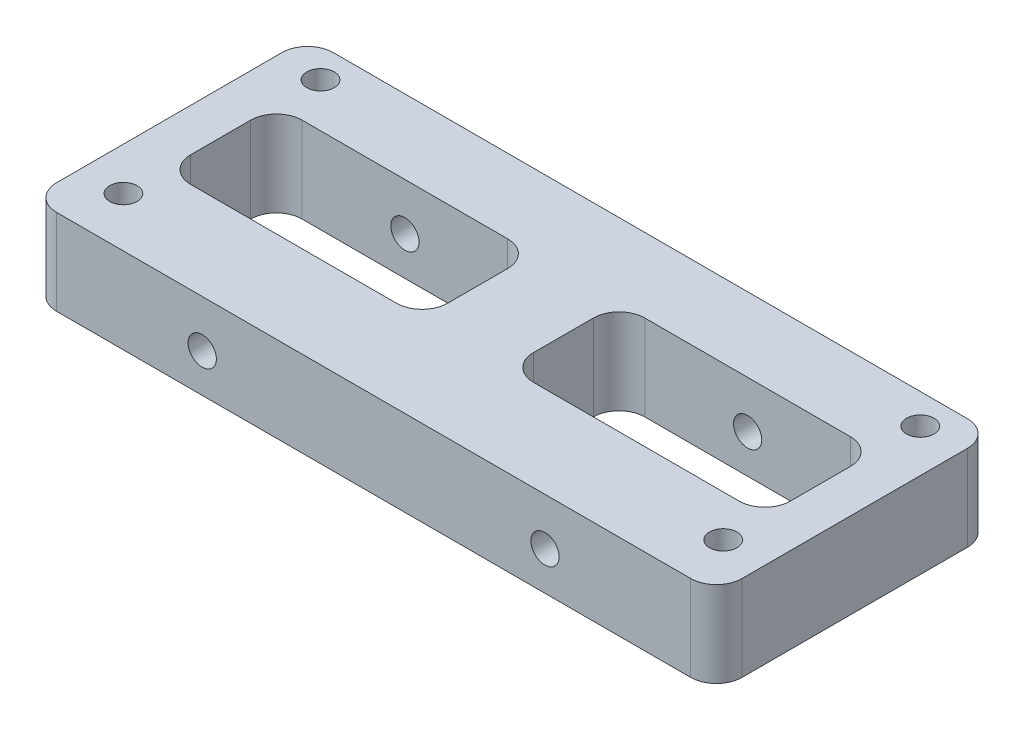
SolidWorks part; units mm, degrees
material "ABS"
ref_plane "前视基准面" through (0, 0, 0) normal (0, 0, 1) x (1, 0, 0)
ref_plane "上视基准面" through (0, 0, 0) normal (0, 1, 0) x (1, 0, 0)
ref_plane "右视基准面" through (0, 0, 0) normal (1, 0, 0) x (0, 0, -1)
other "Configuration Table"
sketch "草图1" plane through (0, 0, 0) normal (0, 1, 0) x (1, 0, 0)
  line L0 (-50.2114, 11.65) -> (54.5041, 11.65) construction
  line L1 (-40, -17.15) -> (40, -17.15) construction
  line L2 (-40, -17.15) -> (-40, 17.15)
  line L3 (-40, 17.15) -> (40, 17.15)
  line L4 (40, -17.15) -> (40, 17.15)
  line L5 (-40, -17.15) -> (40, 17.15) construction
  line L6 (-40, 17.15) -> (40, -17.15) construction
  line L7 (-47.7398, -11.35) -> (53.8537, -11.35) construction
  line L8 (-35, 11.65) -> (-35, -11.35) construction
  line L9 (0, 39.122) -> (0, -35.2195) construction
  line L10 (-40, -17.15) -> (-20, -17.15)
  line L15 (-15, -6.5) -> (15, 6.5) construction
  line L16 (-15, 6.5) -> (15, -6.5) construction
  line L17 (-20, -17.15) -> (20, -17.15) construction
  line L24 (-20, -17.15) -> (20, -17.15)
  line L28 (20, -17.15) -> (40, -17.15)
  line L29 (35, -11.35) -> (35, 11.65) construction
  line L30 (47.8523, 0) -> (-46.2737, 0) construction
  line L31 (-35, 6.5) -> (-5, 6.5)
  line L32 (-35, 6.5) -> (-35, -6.5)
  line L33 (-35, -6.5) -> (-5, -6.5)
  line L34 (-5, 6.5) -> (-5, -6.5)
  line L35 (5, 6.5) -> (5, -6.5)
  line L36 (35, -6.5) -> (5, -6.5)
  line L37 (35, 6.5) -> (35, -6.5)
  line L38 (35, 6.5) -> (5, 6.5)
  circle A0 centre (-35, 11.65) radius 1.6
  circle A1 centre (-35, -11.35) radius 1.6
  circle A2 centre (35, -11.35) radius 1.6
  circle A3 centre (35, 11.65) radius 1.6
  point P0 (0, 0)
  point P20 (0, 0)
  dimension "D5" = 3.2
  dimension "D6" = 70
  dimension "D1" = 80
  dimension "D2" = 5.5
  dimension "D3" = 23
  dimension "D4" = 5.8
  dimension "D7" = 13
  dimension "D8" = 30
  dimension "D9" = 35
  dimension "D10" = 13
  dimension "D11" = 30
extrude "凸台-拉伸1" add sketch "草图1" along normal blind 10
sketch "草图2" plane through (0, 0, -17.15) normal (0, 0, -1) x (-1, 0, 0)
  line L0 (0, 23.9833) -> (0, -13.9833) construction
  line L1 (-40, 0) -> (40, 0) construction
  line L2 (-63.4306, 4.5) -> (25.1964, 4.5) construction
  line L3 (-40, 10) -> (-40, 0) construction
  circle A0 centre (-20, 4.5) radius 1.65
  circle A1 centre (20, 4.5) radius 1.65
  dimension "D1" = 3.3
  dimension "D2" = 4.5
  dimension "D3" = 20
extrude "切除-拉伸1" cut sketch "草图2" against normal through all
sketch "草图4" plane through (0, 0, -17.15) normal (0, 0, -1) x (-1, 0, 0)
  line L0 (0, 26.7715) -> (0, -19.0655) construction
  circle A0 centre (-20, 4.5) radius 3
  circle A1 centre (20, 4.5) radius 3
  dimension "D1" = 6
extrude "切除-拉伸3" cut sketch "草图4" against normal blind 5
sketch "草图6" plane through (0, 10, 0) normal (0, 1, 0) x (1, 0, 0)
  line L0 (40, -17.15) -> (40, 17.15) construction
  line L1 (-40, 17.15) -> (40, 17.15)
  line L2 (-40, 17.15) -> (-40, 15.15)
  line L3 (-40, 15.15) -> (40, 15.15)
  line L4 (40, 17.15) -> (40, 15.15)
  dimension "D1" = 2
extrude "切除-拉伸5" cut sketch "草图6" against normal through all
fillet "圆角1" radius 3 12 edges at (40, 5, 17.15) (-40, 5, 17.15) (40, 5, -15.15) (-40, 5, -15.15) (5, 5, -6.5) (5, 5, 6.5) (35, 5, 6.5) (35, 5, -6.5) (-35, 5, 6.5) (-5, 5, 6.5) (-5, 5, -6.5) (-35, 5, -6.5)
